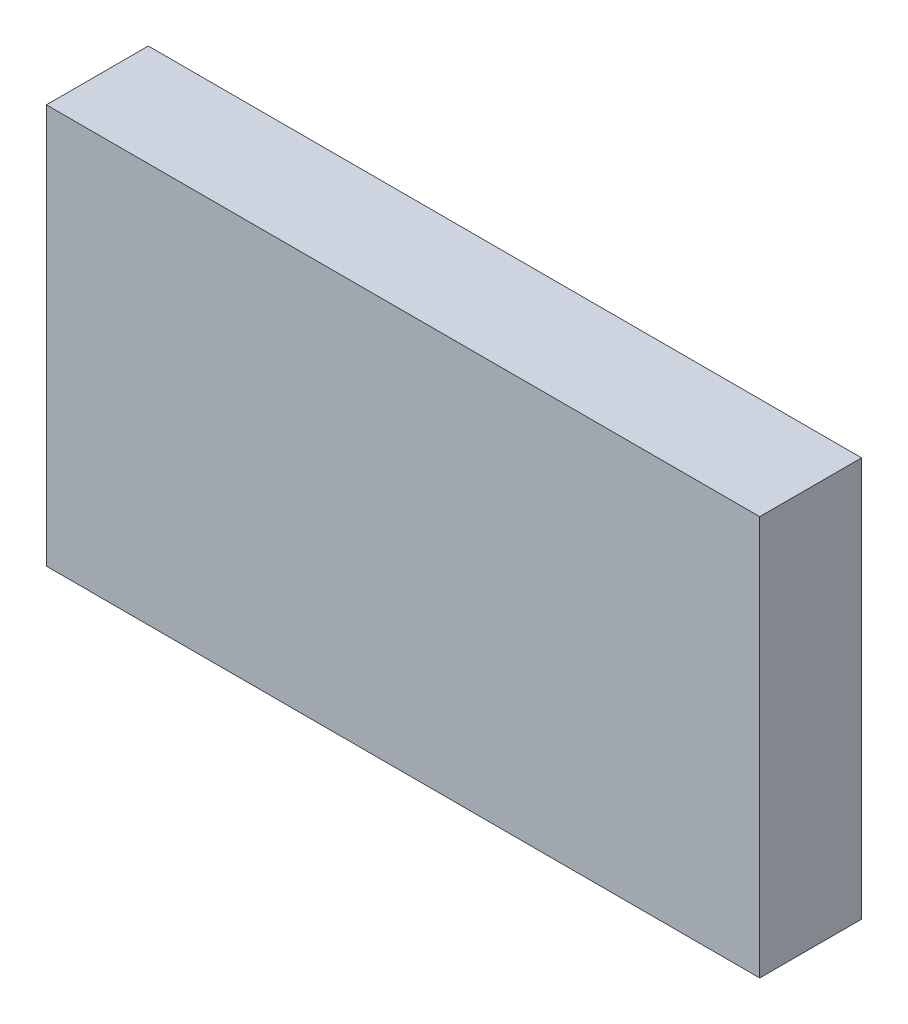
SolidWorks part; units mm, degrees
ref_plane "Ön Düzlem" through (0, 0, 0) normal (0, 0, 1) x (1, 0, 0)
ref_plane "Üst Düzlem" through (0, 0, 0) normal (0, 1, 0) x (1, 0, 0)
ref_plane "Sağ Düzlem" through (0, 0, 0) normal (1, 0, 0) x (0, 0, -1)
sketch "Çizim1" plane through (0, 0, 0) normal (0, 0, 1) x (1, 0, 0)
  line L1 (0, 0) -> (70.0225, 0)
  line L2 (0, 0) -> (0, -39.2206)
  line L3 (0, -39.2206) -> (70.0225, -39.2206)
  line L4 (70.0225, 0) -> (70.0225, -39.2206)
extrude "Yükseklik-Ekstrüzyon1" add sketch "Çizim1" along normal blind 10
